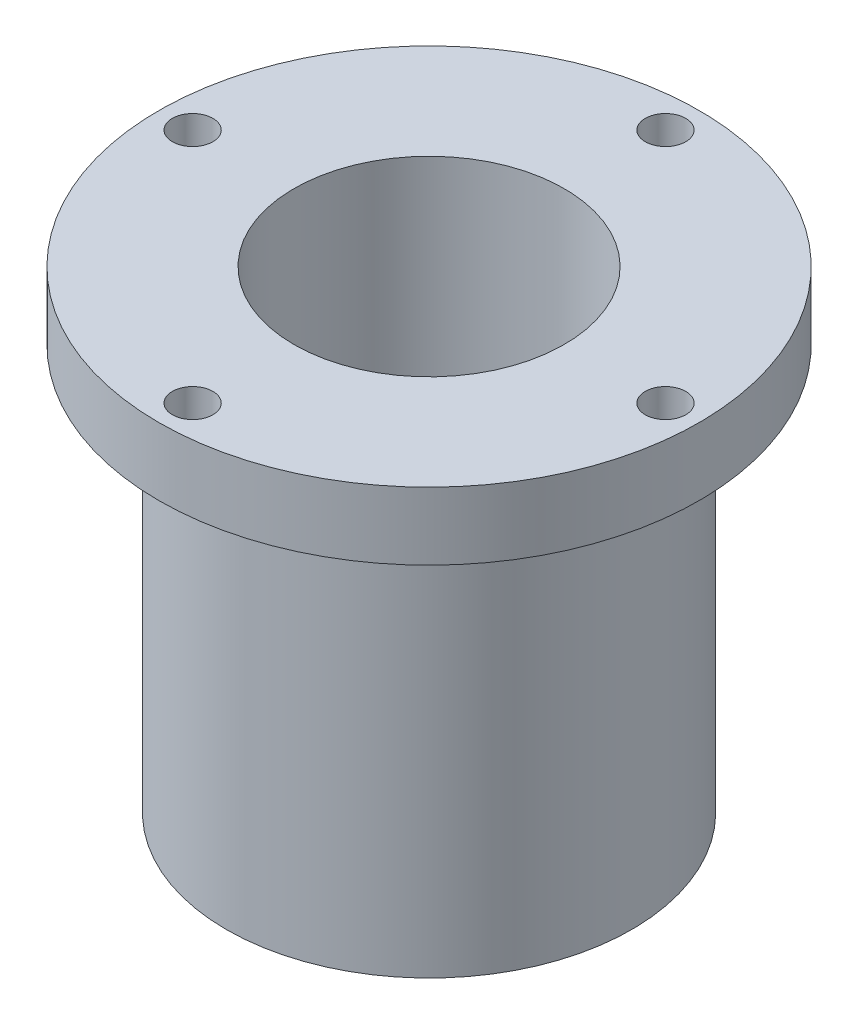
SolidWorks part; units mm, degrees
ref_plane "前视基准面" through (0, 0, 0) normal (0, 0, 1) x (1, 0, 0)
ref_plane "上视基准面" through (0, 0, 0) normal (0, 1, 0) x (1, 0, 0)
ref_plane "右视基准面" through (0, 0, 0) normal (1, 0, 0) x (0, 0, -1)
sketch "草图1" plane through (0, 0, 0) normal (0, 1, 0) x (1, 0, 0)
  circle A0 centre (0, 0) radius 10
  circle A1 centre (0, 0) radius 15
  dimension "D1" = 20
  dimension "D2" = 30
extrude "凸台-拉伸1" add sketch "草图1" along normal blind 30
sketch "草图2" plane through (0, 30, 0) normal (0, 1, 0) x (1, 0, 0)
  circle A0 centre (0, 0) radius 20
  circle M1 centre (0, 0) radius 15
  circle M2 centre (0, 0) radius 10
  dimension "D1" = 40
extrude "凸台-拉伸2" add sketch "草图2" along normal blind 5 contours M1 M2 | A0 M1
sketch "草图3" plane through (0, 35, 0) normal (0, 1, 0) x (1, 0, 0)
  circle A0 centre (0, 0) radius 17.5 construction
  point P3 (17.5, 0)
  point P7 (0, -17.5)
  point P8 (-17.5, 0)
  point P9 (0, 17.5)
  dimension "D1" = 35
  dimension "D2" = 4
hole_wizard "Ø3.0mm 暗销孔1" positions "草图3" profile "草图5" hole size "Ø3.0" standard "GB"
sketch "草图5" plane through (0, 35, -17.5) normal (1, 0, 0) x (0, 0, 1)
  line L0 (0, 0) -> (0, 8.4013)
  line L1 (0, 8.4013) -> (1.5, 7.5)
  line L2 (1.5, 7.5) -> (1.5, 0)
  line L5 (1.5, 0) -> (0, 0)
  line L10 (0, 8.4013) -> (-1.5, 7.5) construction
  line L11 (0, -6.35) -> (0, 107.95) construction
  dimension "孔直径" = 3
  dimension "孔深度" = 7.5
  dimension "导头角度" = 118
